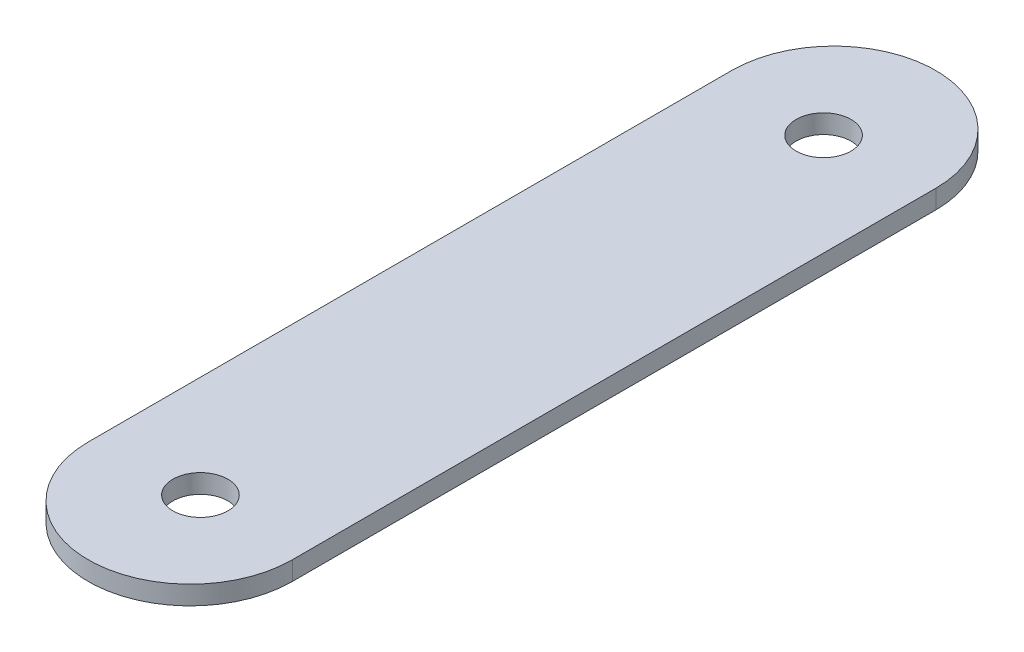
SolidWorks part; units mm, degrees
ref_plane "前视基准面" through (0, 0, 0) normal (0, 0, 1) x (1, 0, 0)
ref_plane "上视基准面" through (0, 0, 0) normal (0, 1, 0) x (1, 0, 0)
ref_plane "右视基准面" through (0, 0, 0) normal (1, 0, 0) x (0, 0, -1)
other "Configuration Table"
ref_plane "基准面1" through (0, 0, 0) normal (0, -1, 0) x (1, 0, 0)
sketch "草图1" plane through (0, 0, 0) normal (0, -1, 0) x (1, 0, 0)
  line L0 (6.5, -20.5) -> (6.5, 20.5)
  line L1 (-6.5, 20.5) -> (-6.5, -20.5)
  arc A0 (6.5, 20.5) -> (-6.5, 20.5) centre (0, 20.5) ccw
  arc A1 (-6.5, -20.5) -> (6.5, -20.5) centre (0, -20.5) ccw
  circle A2 centre (0, 19.85) radius 1.75
  circle A3 centre (0, -19.85) radius 1.75
  dimension "D1" = 3.5
  dimension "D2" = 3.5
  dimension "D3" = 6.5
  dimension "D4" = 0.65
  dimension "D5" = 40.35
  dimension "D6" = 41
extrude "凸台-拉伸1" add sketch "草图1" against normal blind 1.2
